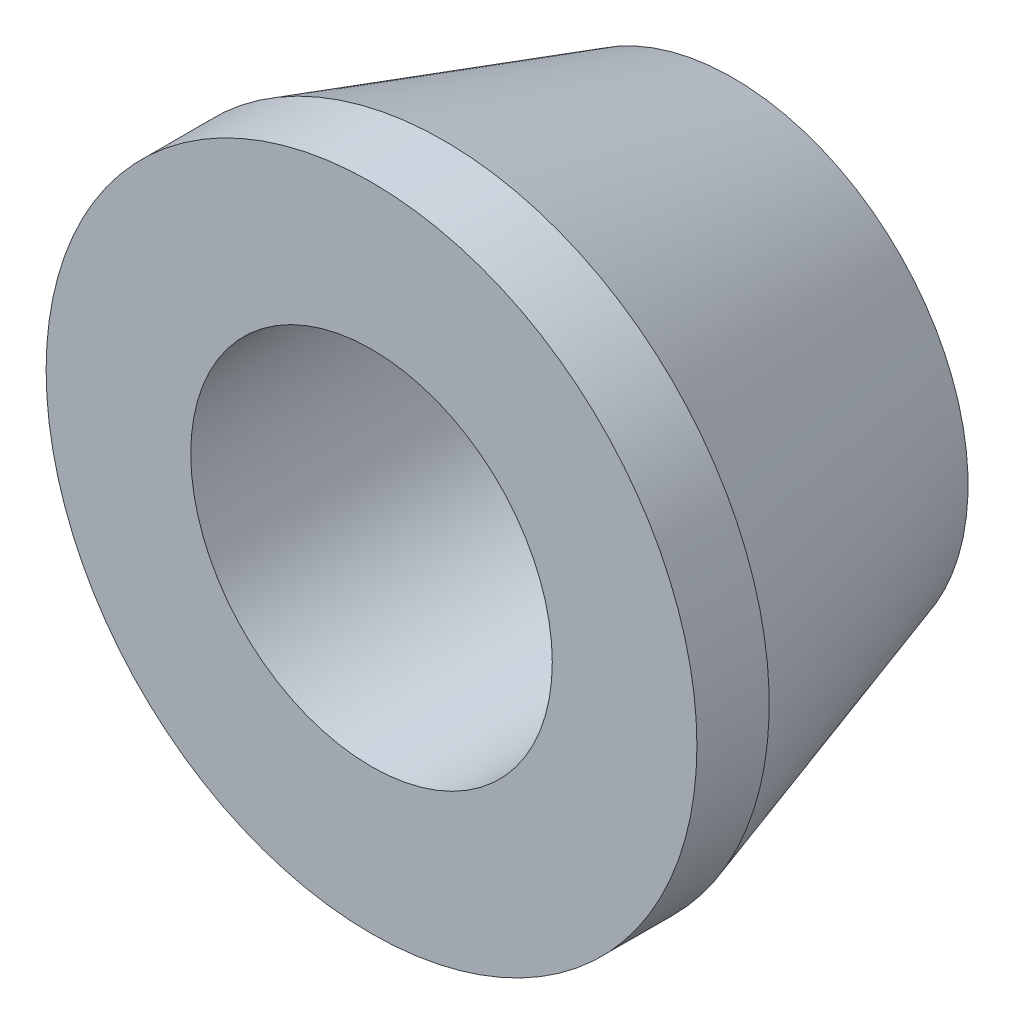
SolidWorks part; units mm, degrees
ref_plane "Płaszczyzna przednia" through (0, 0, 0) normal (0, 0, 1) x (1, 0, 0)
ref_plane "Płaszczyzna górna" through (0, 0, 0) normal (0, 1, 0) x (1, 0, 0)
ref_plane "Płaszczyzna prawa" through (0, 0, 0) normal (1, 0, 0) x (0, 0, -1)
sketch "Sketch1" plane through (0, 0, 0) normal (0, 0, 1) x (1, 0, 0)
  circle A0 centre (0, 0) radius 5
  circle A1 centre (0, 0) radius 9
  dimension "D1" = 10
  dimension "D2" = 18
extrude "Boss-Extrude1" add sketch "Sketch1" along normal blind 2
ref_plane "Plane1" through (0, 0, -8) normal (0, 0, -1) x (-1, 0, 0)
sketch "Sketch2" plane through (0, 0, -8) normal (0, 0, -1) x (-1, 0, 0)
  circle A0 centre (0, 0) radius 5
  circle A1 centre (0, 0) radius 6.5
  dimension "D1" = 10
  dimension "D2" = 1.5
sketch "Sketch3" plane through (0, 0, 0) normal (0, 0, -1) x (-1, 0, 0)
  circle A0 centre (0, 0) radius 5 construction
  circle A1 centre (0, 0) radius 9
  circle A2 centre (0, 0) radius 9
  circle A3 centre (0, 0) radius 5
  dimension "D1" = 0
loft "Loft1" add section "Sketch3" section "Sketch2"
sketch "Sketch4" plane through (0, 0, -8) normal (0, 0, -1) x (-1, 0, 0)
  circle A0 centre (0, 0) radius 5
  dimension "D1" = 10
extrude "Cut-Extrude1" cut sketch "Sketch4" against normal up to surface (10 mm away) up to face at (9, 0, 2)
